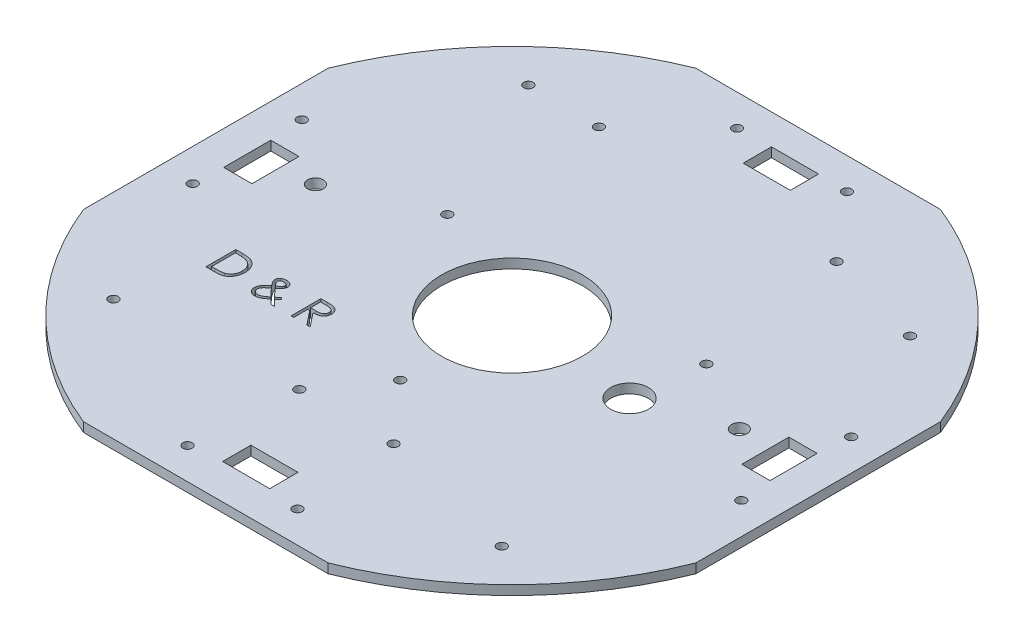
SolidWorks part; units mm, degrees
ref_plane "Front Plane" through (0, 0, 0) normal (0, 0, 1) x (1, 0, 0)
ref_plane "Top Plane" through (0, 0, 0) normal (0, 1, 0) x (1, 0, 0)
ref_plane "Right Plane" through (0, 0, 0) normal (1, 0, 0) x (0, 0, -1)
sketch "Sketch1" plane through (0, 0, 0) normal (0, 1, 0) x (1, 0, 0)
  line L1 (-97.5, -97.5) -> (97.5, -97.5)
  line L2 (-97.5, -97.5) -> (-97.5, 97.5)
  line L3 (-97.5, 97.5) -> (97.5, 97.5)
  line L4 (97.5, -97.5) -> (97.5, 97.5)
  line L5 (-97.5, -97.5) -> (97.5, 97.5) construction
  line L6 (-97.5, 97.5) -> (97.5, -97.5) construction
  point P0 (0, 0)
  dimension "D1" = 195
  dimension "D2" = 195
sketch "Sketch2" plane through (0, 0, 0) normal (0, 1, 0) x (1, 0, 0)
  line L0 (-97.5, -97.5) -> (97.5, 97.5) construction
  circle A0 centre (0, 0) radius 105
  circle A1 centre (0, 0) radius 177.8364
  dimension "D1" = 210
extrude "Plate" add sketch "Sketch1" along normal blind 3
extrude "Outline" cut sketch "Sketch2" along normal blind 30
sketch "Sketch6" plane through (0, 0, 0) normal (0, 1, 0) x (1, 0, 0)
  line L0 (-97.5, 38.9711) -> (-97.5, -38.9711) construction
  line L1 (38.9711, 97.5) -> (-38.9711, 97.5) construction
  circle A0 centre (0, 0) radius 22.4489
  dimension "D1" = 97.5
  dimension "D2" = 97.5
extrude "Middle Circle" cut sketch "Sketch6" along normal blind 145
sketch "Ping Sensor and Arduino Holes" plane through (0, 3, 0) normal (0, 1, 0) x (1, 0, 0)
  line L0 (-97.5, 38.9711) -> (-97.5, -38.9711) construction
  line L1 (-38.9711, -97.5) -> (38.9711, -97.5) construction
  line L2 (97.5, -38.9711) -> (97.5, 38.9711) construction
  line L3 (38.9711, 97.5) -> (-38.9711, 97.5) construction
  circle A0 centre (87.4796, 20.55) radius 1.5
  circle A1 centre (87.5, -14.45) radius 1.5
  circle A2 centre (19.1771, -87.5) radius 1.5
  circle A3 centre (-15.8229, -87.5) radius 1.5
  circle A4 centre (-87.5, 20.55) radius 1.5
  circle A5 centre (-87.2407, -14.4491) radius 1.5
  circle A6 centre (-15.8229, 87.5) radius 1.5
  circle A7 centre (19.1771, 87.5) radius 1.5
  circle A8 centre (-38.187, 17.5868) radius 1.5
  circle A9 centre (44.313, 17.5868) radius 1.5
  circle A10 centre (-38.202, 65.8868) radius 1.5
  circle A11 centre (36.7947, 66.5868) radius 1.5
  dimension "D1" = 35
  dimension "D2" = 35
  dimension "D3" = 35
  dimension "D4" = 35
  dimension "D9" = 82.5
  dimension "D10" = 75
  dimension "D12" = 3
  dimension "D13" = 3
  dimension "D14" = 3
  dimension "D15" = 3
  dimension "D16" = 3
  dimension "D17" = 3
  dimension "D18" = 3
  dimension "D19" = 3
  dimension "D20" = 3
  dimension "D21" = 3
  dimension "D22" = 3
  dimension "D23" = 3
  dimension "D5" = 10
  dimension "D6" = 10
  dimension "D7" = 10
  dimension "D8" = 10
  dimension "D11" = 48.3
  dimension "D24" = 49
sketch "Stands" plane through (0, 3, 0) normal (0, 1, 0) x (1, 0, 0)
  circle A0 centre (61.9949, -65.2429) radius 1.5
  circle A1 centre (-68.0051, -58.9517) radius 1.5
  circle A2 centre (-60.9774, 66.1948) radius 1.5
  circle A3 centre (69.0226, 57.7571) radius 1.5
  dimension "D1" = 90
  dimension "D4" = 90
  dimension "D9" = 3
  dimension "D10" = 3
  dimension "D11" = 3
  dimension "D12" = 3
  dimension "D2" = 90
  dimension "D3" = 130
  dimension "D5" = 90
  dimension "D6" = 130
  dimension "D7" = 125.1465
  dimension "D8" = 123
extrude "Ping and Arduino" cut sketch "Ping Sensor and Arduino Holes" against normal blind 30
extrude "Stand" cut sketch "Stands" against normal blind 30
sketch "Sketch8" plane through (0, 3, 0) normal (0, 1, 0) x (1, 0, 0)
  line L0 (-97.5, 38.9711) -> (-97.5, -38.9711) construction
  line L1 (97.5, -38.9711) -> (97.5, 38.9711) construction
  circle A0 centre (-67.5, 4.9039) radius 2.5
  circle A1 centre (67.5, 4.9039) radius 2.5
  dimension "D1" = 30
  dimension "D3" = 5
  dimension "D4" = 5
  dimension "D2" = 30
extrude "Handles" cut sketch "Sketch8" against normal blind 30
sketch "Sketch9" plane through (0, 3, 0) normal (0, 1, 0) x (1, 0, 0)
  circle A0 centre (0, -35.6007) radius 1.5
  dimension "D1" = 3
extrude "Compass" cut sketch "Sketch9" against normal blind 10
sketch "Sketch10" plane through (0, 3, 0) normal (0, 1, 0) x (1, 0, 0)
  circle A0 centre (41.5596, -4.1254) radius 6
  dimension "D1" = 12
extrude "Power Supply" cut sketch "Sketch10" against normal blind 10
sketch "Sketch13" plane through (0, 3, 0) normal (0, 1, 0) x (1, 0, 0)
  line L0 (-66.6176, -35.2951) -> (-25.058, -35.2951) construction
  text T0 "D & R" font "Century Gothic" height in points 36
extrude "Cut-Extrude5" cut sketch "Sketch13" against normal blind 10
sketch "Sketch14" plane through (0, 3, 0) normal (0, 1, 0) x (1, 0, 0)
  line L1 (-77.7862, -5.0422) -> (-86.7862, -5.0422)
  line L2 (-77.7862, -5.0422) -> (-77.7862, 9.9578)
  line L3 (-77.7862, 9.9578) -> (-86.7862, 9.9578)
  line L4 (-86.7862, -5.0422) -> (-86.7862, 9.9578)
  line L5 (9.1676, -86.3278) -> (-5.8324, -86.3278)
  line L6 (9.1676, -86.3278) -> (9.1676, -77.3278)
  line L7 (9.1676, -77.3278) -> (-5.8324, -77.3278)
  line L8 (-5.8324, -86.3278) -> (-5.8324, -77.3278)
  line L9 (86.6186, -4.431) -> (77.6186, -4.431)
  line L10 (86.6186, -4.431) -> (86.6186, 10.569)
  line L11 (86.6186, 10.569) -> (77.6186, 10.569)
  line L12 (77.6186, -4.431) -> (77.6186, 10.569)
  line L13 (9.7787, 87.8558) -> (-5.2213, 87.8558)
  line L14 (9.7787, 87.8558) -> (9.7787, 78.8558)
  line L15 (9.7787, 78.8558) -> (-5.2213, 78.8558)
  line L16 (-5.2213, 87.8558) -> (-5.2213, 78.8558)
  dimension "D1" = 15
  dimension "D2" = 9
  dimension "D3" = 15
  dimension "D4" = 9
  dimension "D5" = 9
  dimension "D6" = 15
  dimension "D7" = 15
  dimension "D8" = 9
extrude "Cut-Extrude6" cut sketch "Sketch14" against normal blind 10
sketch "Sketch15" plane through (0, 3, 0) normal (0, 1, 0) x (1, 0, 0)
  circle A0 centre (-13.4984, -54.242) radius 1.5
  circle A1 centre (16.5016, -54.2148) radius 1.5
  dimension "D1" = 3
  dimension "D2" = 3
  dimension "D3" = 30
extrude "Cut-Extrude7" cut sketch "Sketch15" against normal blind 10
